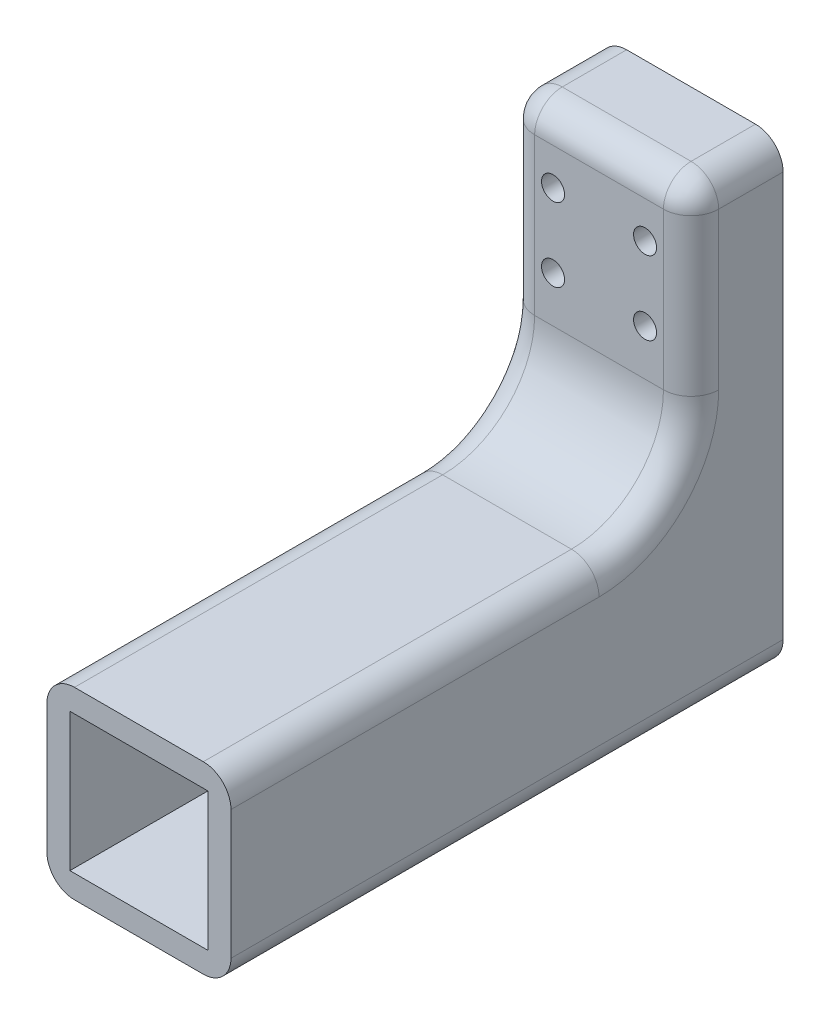
SolidWorks part; units mm, degrees
ref_plane "正面" through (0, 0, 0) normal (0, 0, 1) x (1, 0, 0)
ref_plane "平面" through (0, 0, 0) normal (0, 1, 0) x (1, 0, 0)
ref_plane "右側面" through (0, 0, 0) normal (1, 0, 0) x (0, 0, -1)
sketch "ｽｹｯﾁ4" plane through (0, 0, 0) normal (0, 0, 1) x (1, 0, 0)
  line L1 (-7.5, 7.5) -> (7.5, 7.5)
  line L2 (-7.5, 7.5) -> (-7.5, -7.5)
  line L3 (-7.5, -7.5) -> (7.5, -7.5)
  line L4 (7.5, 7.5) -> (7.5, -7.5)
  line L5 (-7.5, 7.5) -> (7.5, -7.5) construction
  line L6 (-7.5, -7.5) -> (7.5, 7.5) construction
  line L7 (-10, 10) -> (10, 10)
  line L8 (-10, 10) -> (-10, -10)
  line L9 (-10, -10) -> (10, -10)
  line L10 (10, 10) -> (10, -10)
  line L11 (-10, 10) -> (10, -10) construction
  line L12 (-10, -10) -> (10, 10) construction
  point P0 (0, 0)
  point P6 (0, 0)
  dimension "D1" = 15
  dimension "D2" = 20
  dimension "D3" = 15
  dimension "D4" = 20
extrude "ﾎﾞｽ - 押し出し3" add sketch "ｽｹｯﾁ4" along normal blind 60
sketch "ｽｹｯﾁ5" plane through (0, 0, 0) normal (0, 0, 1) x (1, 0, 0)
  line L0 (10, 10) -> (10, 40)
  line L1 (10, 40) -> (-10, 40)
  line L2 (-10, 40) -> (-10, 10)
  line L3 (-10, 10) -> (10, 10)
  dimension "D1" = 40
extrude "ﾎﾞｽ - 押し出し4" add sketch "ｽｹｯﾁ5" along normal blind 10
hole_wizard "M3x0.5 ねじ穴1" positions "ｽｹｯﾁ6" profile "ｽｹｯﾁ7" tap size "M3x0.5" standard "JIS" end condition through all
sketch "ｽｹｯﾁ6" plane through (0, 0, 0) normal (0, 0, -1) x (-1, 0, 0)
  point P0 (-5, 25)
  point P2 (-5, 33)
  point P4 (5, 33)
  point P6 (5, 25)
  dimension "D1" = 25
  dimension "D2" = 25
  dimension "D3" = 8
  dimension "D4" = 8
  dimension "D5" = 5
  dimension "D6" = 5
sketch "ｽｹｯﾁ7" plane through (5, 25, 0) normal (1, 0, 0) x (0, 1, 0)
  line L0 (0, 0) -> (0, 60)
  line L1 (0, 60) -> (1.25, 60)
  line L2 (1.25, 60) -> (1.25, 0)
  line L5 (1.25, 0) -> (0, 0)
  line L11 (0, -6.35) -> (0, 107.95) construction
  dimension "次ｻｰﾌｪｽまでのねじ下穴ﾄﾞﾘﾙ直径" = 2.5
  dimension "次ｻｰﾌｪｽまでのねじ下穴ﾄﾞﾘﾙの深さ" = 60
cosmetic thread "穴のねじ山1" parameters "D2"=3
cosmetic thread "穴のねじ山2" parameters "D2"=3
cosmetic thread "穴のねじ山3" parameters "D2"=3
cosmetic thread "穴のねじ山4" parameters "D2"=3
fillet "ﾌｨﾚｯﾄ1" radius 10 1 edges at (0, 10, 10)
fillet "ﾌｨﾚｯﾄ2" radius 3 9 edges at (-10, 30, 10) (-10, 12.9289, 12.9289) (10, 30, 10) (10, 12.9289, 12.9289) (0, 40, 10) (10, 40, 5) (-10, 40, 5) (-10, 10, 40) (10, 10, 40)
fillet "ﾌｨﾚｯﾄ3" radius 3 2 edges at (10, -10, 30) (-10, -10, 30)
